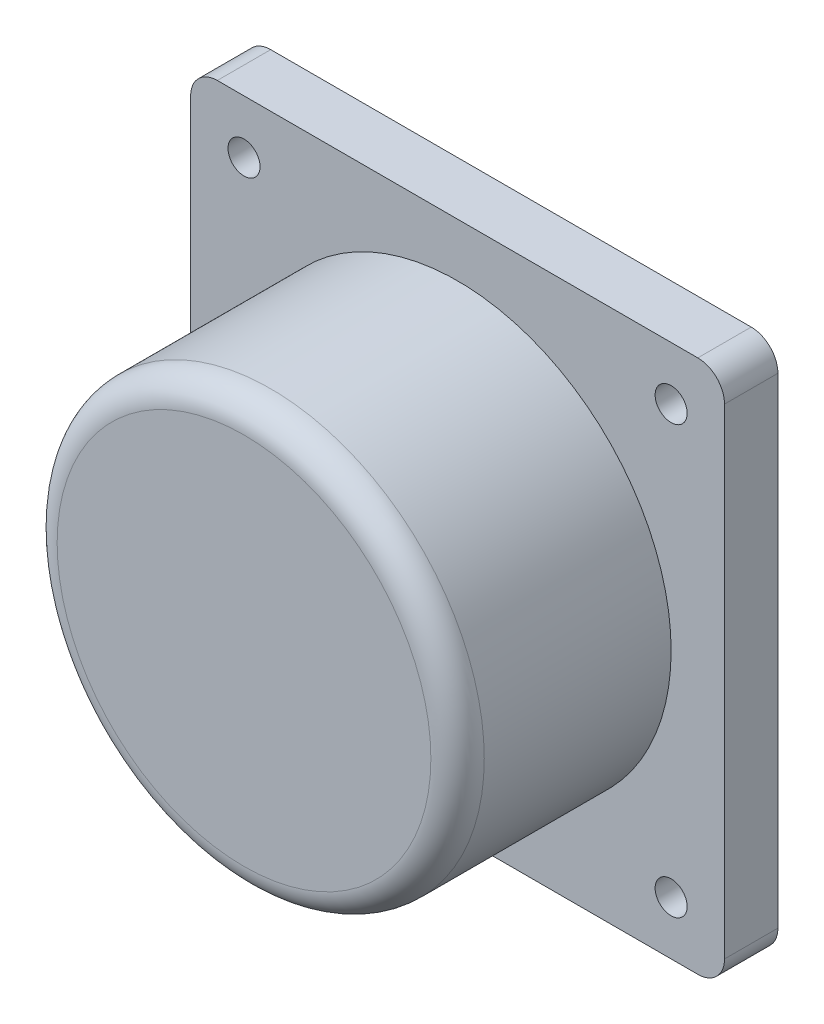
SolidWorks part; units mm, degrees
ref_plane "Front Plane" through (0, 0, 0) normal (0, 0, 1) x (1, 0, 0)
ref_plane "Top Plane" through (0, 0, 0) normal (0, 1, 0) x (1, 0, 0)
ref_plane "Right Plane" through (0, 0, 0) normal (1, 0, 0) x (0, 0, -1)
sketch "Sketch1" plane through (0, 0, 0) normal (0, 0, 1) x (1, 0, 0)
  line L0 (0, -55) -> (0, 55) construction
  line L1 (-50, -50) -> (50, -50)
  line L2 (-50, -50) -> (-50, 50)
  line L3 (-50, 50) -> (50, 50)
  line L4 (50, -50) -> (50, 50)
  line L5 (-50, -50) -> (50, 50) construction
  line L6 (-50, 50) -> (50, -50) construction
  line L7 (-40, -40) -> (40, -40) construction
  line L8 (-40, -40) -> (-40, 40) construction
  line L9 (-40, 40) -> (40, 40) construction
  line L10 (40, -40) -> (40, 40) construction
  line L11 (-40, -40) -> (40, 40) construction
  line L12 (-40, 40) -> (40, -40) construction
  line L13 (55, 0) -> (-55, 0) construction
  circle A0 centre (40, 40) radius 3
  circle A1 centre (-40, 40) radius 3
  circle A2 centre (-40, -40) radius 3
  circle A3 centre (40, -40) radius 3
  point P0 (0, 0)
  point P6 (0, 0)
  dimension "D3" = 6
  dimension "D1" = 100
  dimension "D2" = 100
  dimension "D4" = 10
extrude "Boss-Extrude1" add sketch "Sketch1" along normal blind 10
sketch "Sketch2" plane through (0, 0, 10) normal (0, 0, 1) x (1, 0, 0)
  circle A0 centre (0, 0) radius 40
extrude "Boss-Extrude2" add sketch "Sketch2" along normal blind 40
fillet "Fillet1" radius 5 5 edges at (50, 50, 5) (-50, 50, 5) (-50, -50, 5) (50, -50, 5) (40, 0, 50)
